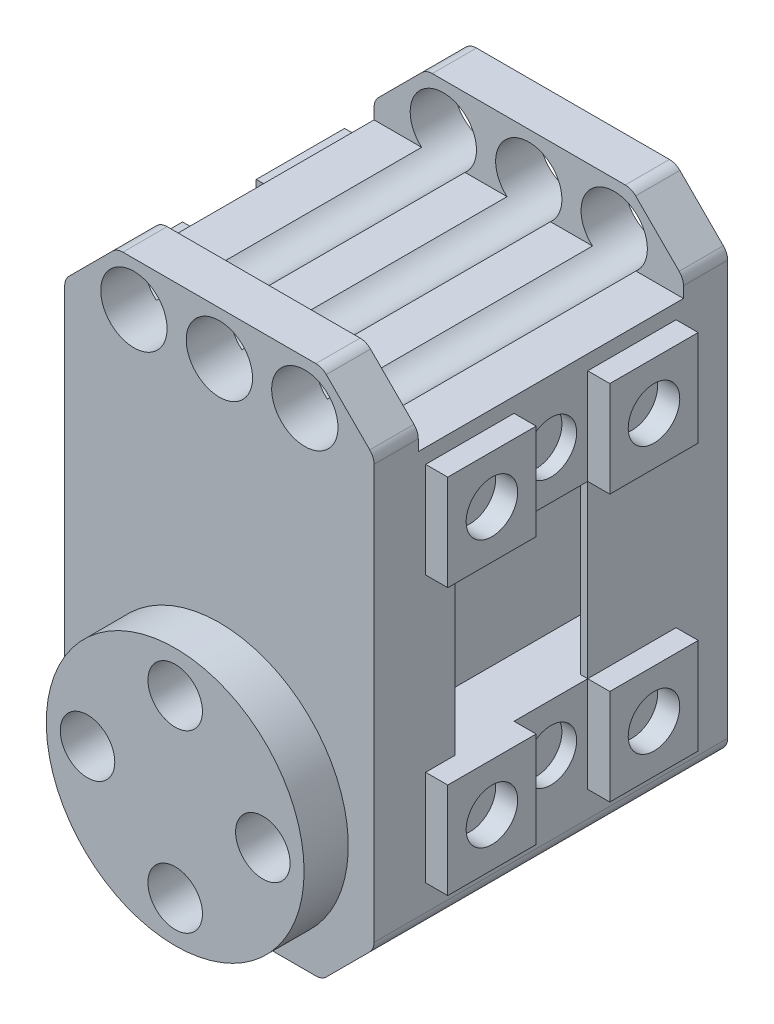
SolidWorks part; units mm, degrees
ref_plane "Plan de face" through (0, 0, 0) normal (0, 0, 1) x (1, 0, 0)
ref_plane "Plan de dessus" through (0, 0, 0) normal (0, 1, 0) x (1, 0, 0)
ref_plane "Plan de droite" through (0, 0, 0) normal (1, 0, 0) x (0, 0, -1)
sketch "Esquisse1" plane through (0, 0, 0) normal (0, 0, 1) x (1, 0, 0)
  line L0 (3.191, -0.1556) -> (-0.3445, 3.3799)
  line L1 (-0.3445, 3.3799) -> (-0.3445, 32.3088)
  line L2 (-0.3445, 32.3088) -> (3.191, 35.8444)
  line L3 (3.191, 35.8444) -> (17.12, 35.8444)
  line L4 (17.12, 35.8444) -> (20.6555, 32.3088)
  line L5 (20.6555, 32.3088) -> (20.6555, 3.3799)
  line L6 (20.6555, 3.3799) -> (17.12, -0.1556)
  line L7 (17.12, -0.1556) -> (3.191, -0.1556)
  dimension "D1" = 21
  dimension "D2" = 36
  dimension "D3" = 5
  dimension "D4" = 5
  dimension "D5" = 5
  dimension "D6" = 5
extrude "Boss.-Extru.1" add sketch "Esquisse1" along normal blind 24
fillet "Congé1" radius 1 8 edges at (20.6555, 3.3799, 12) (17.12, -0.1556, 12) (-0.3445, 3.3799, 12) (3.191, -0.1556, 12) (-0.3445, 32.3088, 12) (3.191, 35.8444, 12) (17.12, 35.8444, 12) (20.6555, 32.3088, 12)
sketch "Esquisse2" plane through (20.6555, 0, 0) normal (1, 0, 0) x (0, 0, -1)
  line L0 (0, -0.1556) -> (-24, -0.1556) construction
  line L1 (-20.5, 5.5444) -> (-14.5, 5.5444)
  line L2 (-20.5, 5.5444) -> (-20.5, 12.0444)
  line L3 (-20.5, 12.0444) -> (-14.5, 12.0444)
  line L4 (-14.5, 5.5444) -> (-14.5, 12.0444)
  line L17 (-24, 3.7941) -> (-24, 31.8946) construction
  line L18 (-9.5, 5.5444) -> (-3.5, 5.5444)
  line L19 (-9.5, 5.5444) -> (-9.5, 12.0444)
  line L20 (-9.5, 12.0444) -> (-3.5, 12.0444)
  line L21 (-3.5, 5.5444) -> (-3.5, 12.0444)
  line L22 (-20.5, 23.6444) -> (-14.5, 23.6444)
  line L23 (-20.5, 23.6444) -> (-20.5, 30.1444)
  line L24 (-20.5, 30.1444) -> (-14.5, 30.1444)
  line L25 (-14.5, 23.6444) -> (-14.5, 30.1444)
  line L26 (-9.5, 23.6444) -> (-3.5, 23.6444)
  line L27 (-9.5, 23.6444) -> (-9.5, 30.1444)
  line L28 (-9.5, 30.1444) -> (-3.5, 30.1444)
  line L29 (-3.5, 23.6444) -> (-3.5, 30.1444)
  line L30 (0, 3.7941) -> (0, 31.8946) construction
  line L31 (-24, 35.8444) -> (0, 35.8444) construction
  line L32 (-20.5, 5.5444) -> (-14.5, 12.0444) construction
  line L33 (-14.5, 5.5444) -> (-20.5, 12.0444) construction
  line L34 (-9.5, 5.5444) -> (-3.5, 12.0444) construction
  line L35 (-3.5, 5.5444) -> (-9.5, 12.0444) construction
  circle A0 centre (-17.5, 8.7944) radius 1.75
  circle A1 centre (-6.5, 8.7944) radius 1.75
  circle A2 centre (-6.5, 26.8944) radius 1.75
  circle A3 centre (-17.5, 26.8944) radius 1.75
  dimension "D16" = 3.5
  dimension "D17" = 3.5
  dimension "D20" = 3.5
  dimension "D1" = 6.5
  dimension "D2" = 6
  dimension "D3" = 5.7
  dimension "D4" = 3.5
  dimension "D5" = 6.5
  dimension "D6" = 6
  dimension "D7" = 6.5
  dimension "D8" = 6
  dimension "D9" = 6.5
  dimension "D10" = 6
  dimension "D11" = 5.7
  dimension "D12" = 3.5
  dimension "D13" = 3.5
  dimension "D14" = 5.7
  dimension "D15" = 5.7
  dimension "D18" = 3.25
  dimension "D19" = 3.5
extrude "Boss.-Extru.2" add sketch "Esquisse2" along normal blind 1.5
sketch "Esquisse3" plane through (0, 0, 24) normal (0, 0, 1) x (1, 0, 0)
  line L0 (10.1555, -0.1556) -> (10.1555, 35.8444) construction
  line L1 (3.6052, -0.1556) -> (16.7057, -0.1556) construction
  line L2 (16.7057, 35.8444) -> (3.6052, 35.8444) construction
ref_plane "Plan1" through (10.1555, 0, 0) normal (1, 0, 0) x (0, 0, -1)
mirror "Symétrie1" about plane through (10.1555, 0, 0) normal (1, 0, 0) of "Boss.-Extru.2"
sketch "Esquisse4" plane through (10.1555, 0, 0) normal (1, 0, 0) x (0, 0, -1)
  line L1 (-21, 31.1444) -> (-3, 31.1444)
  line L2 (-21, 31.1444) -> (-21, 35.8444)
  line L3 (-21, 35.8444) -> (-3, 35.8444)
  line L4 (-3, 31.1444) -> (-3, 35.8444)
  line L5 (-24, -0.1556) -> (-24, 35.8444) construction
  line L7 (0, 32.6017) -> (0, 35.5515) construction
  dimension "D1" = 4.7
  dimension "D2" = 3
  dimension "D3" = 3
extrude "Enlèv. mat.-Extru.1" cut sketch "Esquisse4" against normal through all both and the other way through all
sketch "Esquisse5" plane through (0, 0, 24) normal (0, 0, 1) x (1, 0, 0)
  line L0 (10.1555, -0.1556) -> (10.1555, 35.8444) construction
  line L1 (16.7057, 35.8444) -> (3.6052, 35.8444) construction
  circle A0 centre (4.3555, 32.8444) radius 2.25
  circle A1 centre (10.1555, 32.8444) radius 2.25
  circle A2 centre (15.9555, 32.8444) radius 2.25
  dimension "D1" = 4.5
  dimension "D2" = 4.5
  dimension "D3" = 4.5
  dimension "D4" = 3
  dimension "D5" = 3
  dimension "D6" = 3
  dimension "D7" = 5.8
  dimension "D8" = 5.8
extrude "Enlèv. mat.-Extru.2" cut sketch "Esquisse5" against normal through all
sketch "Esquisse6" plane through (20.6555, 0, 0) normal (1, 0, 0) x (0, 0, -1)
  line L0 (-20.5, 23.6444) -> (-14.5, 23.6444) construction
  line L1 (-9.5, 12.0444) -> (-18.5, 12.0444)
  line L2 (-9.5, 12.0444) -> (-9.5, 23.6444)
  line L3 (-9.5, 23.6444) -> (-18.5, 23.6444)
  line L4 (-18.5, 12.0444) -> (-18.5, 23.6444)
  dimension "D1" = 9
extrude "Enlèv. mat.-Extru.3" cut sketch "Esquisse6" against normal blind 4
mirror "Symétrie2" about plane through (10.1555, 0, 0) normal (1, 0, 0) of "Enlèv. mat.-Extru.3"
sketch "Esquisse7" plane through (20.6555, 0, 0) normal (1, 0, 0) x (0, 0, -1)
  line L0 (-17.5, 8.7944) -> (-6.5, 8.7944) construction
  line L1 (-17.5, 26.8944) -> (-6.5, 26.8944) construction
  circle A0 centre (-12, 8.7944) radius 1.75
  circle A1 centre (-12, 26.8944) radius 1.75
  dimension "D1" = 3.5
  dimension "D2" = 3.5
extrude "Enlèv. mat.-Extru.4" cut sketch "Esquisse7" against normal blind 1
mirror "Symétrie3" about plane through (10.1555, 0, 0) normal (1, 0, 0) of "Enlèv. mat.-Extru.4"
sketch "Esquisse8" plane through (0, 0, 24) normal (0, 0, 1) x (1, 0, 0)
  line L2 (10.1555, -0.1556) -> (10.1555, 35.8444) construction
  line L3 (3.6052, -0.1556) -> (16.7057, -0.1556) construction
  circle A0 centre (10.1555, 8.5944) radius 8.75
  circle A1 centre (10.1555, 2.6444) radius 1.85
  circle A2 centre (4.2055, 8.5944) radius 1.85
  circle A3 centre (10.1555, 14.5444) radius 1.85
  circle A4 centre (16.1055, 8.5944) radius 1.85
  point P18 (10.1555, 8.5944)
  dimension "D1" = 17.5
  dimension "D2" = 3.7
  dimension "D3" = 2.8
  dimension "D5" = 11.9
  dimension "D4" = 4
extrude "Boss.-Extru.3" add sketch "Esquisse8" along normal blind 3
sketch "Esquisse9" plane through (0, 0, 9.5) normal (0, 0, 1) x (1, 0, 0)
  line L0 (16.6555, 23.6444) -> (20.6555, 23.6444) construction
  line L1 (16.6555, 12.0444) -> (20.1555, 12.0444)
  line L2 (16.6555, 12.0444) -> (16.6555, 23.6444)
  line L3 (16.6555, 23.6444) -> (20.1555, 23.6444)
  line L4 (20.1555, 12.0444) -> (20.1555, 23.6444)
  dimension "D1" = 3.5
extrude "Enlèv. mat.-Extru.5" cut sketch "Esquisse9" against normal blind 4.5
mirror "Symétrie4" about plane through (10.1555, 0, 0) normal (1, 0, 0) of "Enlèv. mat.-Extru.5"
sketch "Esquisse10" plane through (0, 0, 0) normal (0, 0, -1) x (-1, 0, 0)
  line L0 (-10.1555, -0.1556) -> (-10.1555, 35.8444) construction
  line L1 (-3.6052, -0.1556) -> (-16.7057, -0.1556) construction
  circle A0 centre (-10.1555, 8.6944) radius 2.25
  circle A2 centre (-15.9555, 8.6944) radius 2.25
  circle A3 centre (-4.3555, 8.6944) radius 2.25
  dimension "D1" = 4.5
  dimension "D2" = 8.85
  dimension "D3" = 4.5
  dimension "D4" = 4.5
extrude "Enlèv. mat.-Extru.6" cut sketch "Esquisse10" against normal blind 3
